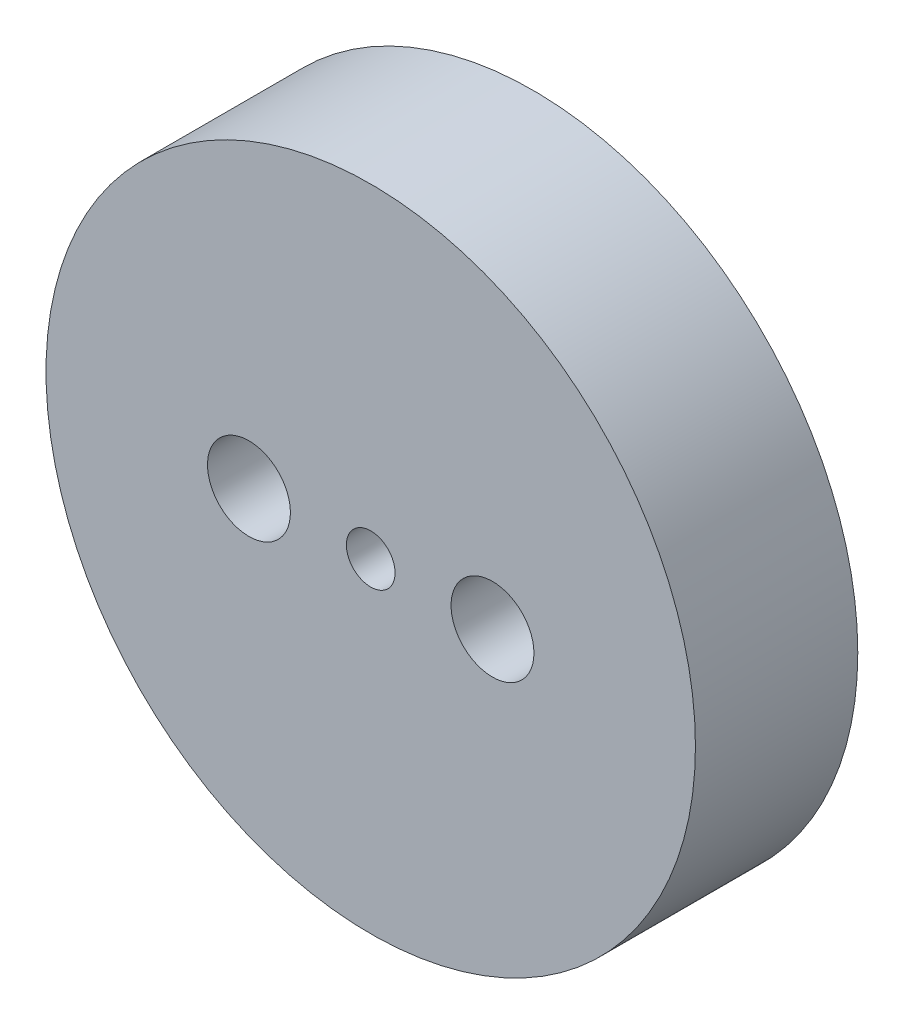
SolidWorks part; units mm, degrees
ref_plane "Front Plane" through (0, 0, 0) normal (0, 0, 1) x (1, 0, 0)
ref_plane "Top Plane" through (0, 0, 0) normal (0, 1, 0) x (1, 0, 0)
ref_plane "Right Plane" through (0, 0, 0) normal (1, 0, 0) x (0, 0, -1)
sketch "Sketch1" plane through (0, 0, 0) normal (0, 0, 1) x (1, 0, 0)
  circle A0 centre (0, 0) radius 20
  circle A1 centre (0, 0) radius 1.5
  dimension "D1" = 40
  dimension "D2" = 3
extrude "Boss-Extrude1" add sketch "Sketch1" along normal blind 10 contours A0
hole_wizard "1/4-20 Tapped Hole1" positions "Sketch2" profile "Sketch3" tap size "1/4-20" standard "ANSI Inch" end condition through all
sketch "Sketch2" plane through (0, 0, 10) normal (0, 0, 1) x (1, 0, 0)
  point P0 (-7.5, 0)
  point P2 (7.5, 0)
  dimension "D1" = 7.5
  dimension "D2" = 7.5
sketch "Sketch3" plane through (-7.5, 0, 10) normal (1, 0, 0) x (0, -1, 0)
  line L0 (0, 0) -> (0, 10)
  line L1 (0, 10) -> (2.5527, 10)
  line L2 (2.5527, 10) -> (2.5527, 0)
  line L5 (2.5527, 0) -> (0, 0)
  line L11 (0, -6.35) -> (0, 107.95) construction
  dimension "Thru Tap Drill Dia." = 5.1054
  dimension "Thru Tap Drill Depth" = 10
cosmetic thread "Hole Thread1"
cosmetic thread "Hole Thread2"
equation "\"D2@Sketch2\"=\"D1@Sketch2\""
